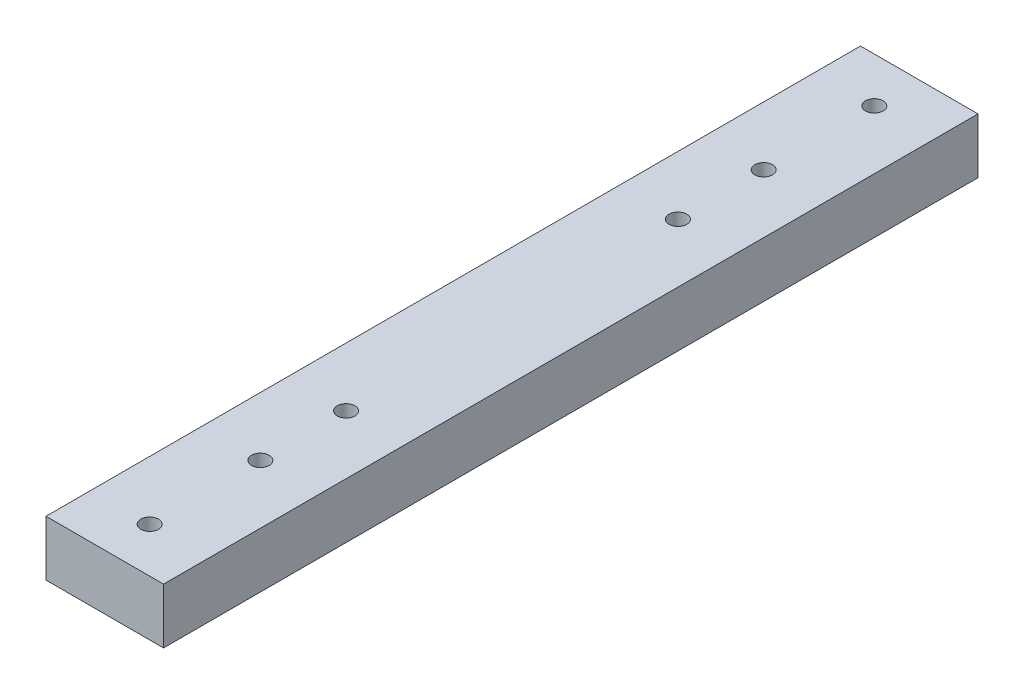
SolidWorks part; units mm, degrees
ref_plane "正面" through (0, 0, 0) normal (0, 0, 1) x (1, 0, 0)
ref_plane "平面" through (0, 0, 0) normal (0, 1, 0) x (1, 0, 0)
ref_plane "右側面" through (0, 0, 0) normal (1, 0, 0) x (0, 0, -1)
sketch "ｽｹｯﾁ1" plane through (0, 5, 0) normal (0, 1, 0) x (1, 0, 0)
  line L0 (7.625, 70.625) -> (-7.625, 70.625)
  line L1 (-7.625, 70.625) -> (-7.625, -70.625)
  line L2 (-7.625, -70.625) -> (7.625, -70.625)
  line L3 (7.625, -70.625) -> (7.625, 70.625)
  line L4 (-7.5, -70.5) -> (7.5, -70.5)
  line L5 (7.5, -70.5) -> (7.5, 70.5)
  line L6 (7.5, 70.5) -> (-7.5, 70.5)
  line L7 (-7.5, 70.5) -> (-7.5, -70.5)
  line L8 (-7.5, -70.5) -> (7.5, -70.5) construction
  line L9 (7.5, -70.5) -> (7.5, 70.5) construction
  line L10 (7.5, 70.5) -> (-7.5, 70.5) construction
  line L11 (-7.5, 70.5) -> (-7.5, -70.5) construction
  circle A1 centre (0, -30) radius 1.6
  circle A2 centre (0, -30) radius 1.6
  circle A3 centre (0, 65.5) radius 1.6
  circle A4 centre (0, 65.5) radius 1.6
  circle A5 centre (0, 45.5) radius 1.6
  circle A6 centre (0, 45.5) radius 1.6
  circle A7 centre (0, -45.5) radius 1.6
  circle A8 centre (0, -45.5) radius 1.6
  circle A9 centre (0, 30) radius 1.6
  circle A10 centre (0, 30) radius 1.6
  circle A11 centre (0, -65.5) radius 1.6
  circle A12 centre (0, -65.5) radius 1.6
  dimension "D1" = 0
  dimension "D2" = 0
  dimension "D3" = 0
  dimension "D4" = 0
  dimension "D5" = 0
  dimension "D6" = 0
  dimension "D7" = 0
  dimension "D8" = 0.125
extrude "ﾎﾞｽ - 押し出し1" add sketch "ｽｹｯﾁ1" along normal blind 5
sketch "ｽｹｯﾁ2" plane through (0, 10, 0) normal (0, 1, 0) x (1, 0, 0)
  line L0 (-10.625, 73.625) -> (-10.625, -73.625)
  line L1 (-10.625, -73.625) -> (10.625, -73.625)
  line L2 (10.625, -73.625) -> (10.625, 73.625)
  line L3 (10.625, 73.625) -> (-10.625, 73.625)
  line L4 (7.625, -70.625) -> (7.625, 70.625)
  line L5 (7.625, 70.625) -> (-7.625, 70.625)
  line L6 (-7.625, 70.625) -> (-7.625, -70.625)
  line L7 (-7.625, -70.625) -> (7.625, -70.625)
  line L8 (7.625, -70.625) -> (7.625, 70.625)
  line L9 (7.625, 70.625) -> (-7.625, 70.625)
  line L10 (-7.625, 70.625) -> (-7.625, -70.625)
  line L11 (-7.625, -70.625) -> (7.625, -70.625)
  dimension "D1" = 0
  dimension "D2" = 3
extrude "ﾎﾞｽ - 押し出し2" add sketch "ｽｹｯﾁ2" against normal blind 10
chamfer "面取り1" distance 2 angle 45 4 edges at (7.625, 0, 0) (0, 0, 70.625) (-7.625, 0, 0) (0, 0, -70.625)
